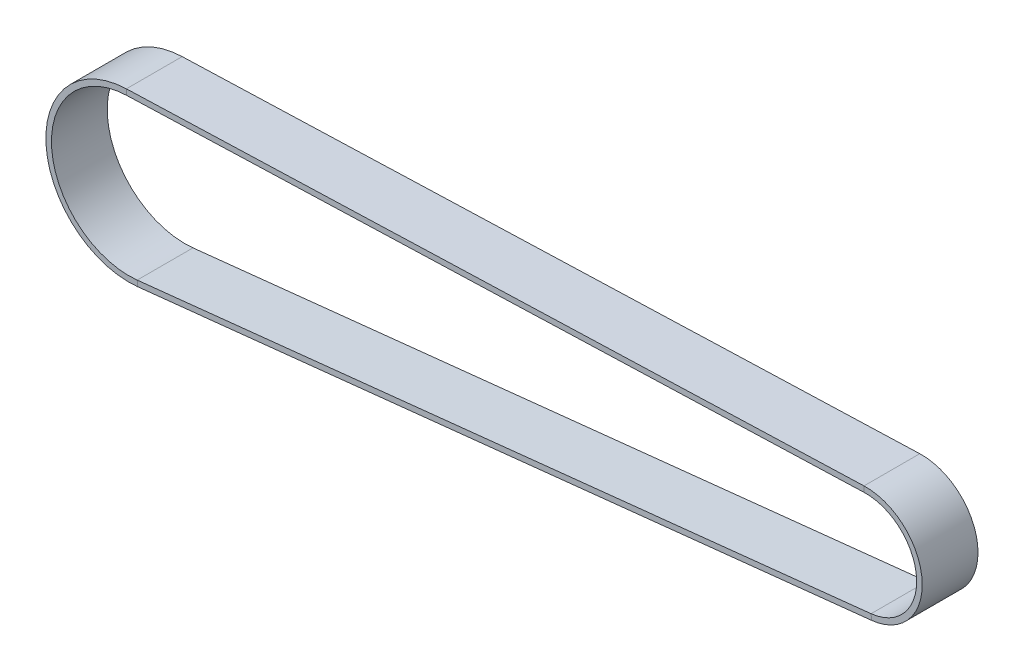
SolidWorks part; units mm, degrees
ref_plane "Alzado" through (0, 0, 0) normal (0, 0, 1) x (1, 0, 0)
ref_plane "Planta" through (0, 0, 0) normal (0, 1, 0) x (1, 0, 0)
ref_plane "Vista lateral" through (0, 0, 0) normal (1, 0, 0) x (0, 0, -1)
sketch "Croquis2" plane through (0, 0, 0) normal (0, 0, 1) x (1, 0, 0)
  line L0 (0, 0) -> (1, 0) construction
  line L1 (0, 0) -> (0, 1) construction
  line L2 (0.9652, -9.0788) -> (-130.6071, -23.0671)
  line L3 (-132.5467, 4.6571) -> (-0.3083, 9.1248)
  arc A0 (-0.3083, 9.1248) -> (0.9652, -9.0788) centre (0, 0) cw
  arc A1 (-130.6071, -23.0671) -> (-132.5467, 4.6571) centre (-132.0772, -9.24) cw
ref_plane "Plano1" through (-0.3083, 0, 0) normal (1, 0, 0) x (0, 0, -1)
sketch "Croquis3" plane through (-0.3083, 0, 0) normal (1, 0, 0) x (0, 0, -1)
  line L1 (-5, 10.1248) -> (5, 10.1248)
  line L2 (-5, 10.1248) -> (-5, 9.1248)
  line L3 (-5, 9.1248) -> (5, 9.1248)
  line L4 (5, 10.1248) -> (5, 9.1248)
  point P4 (0, 9.1248)
  dimension "D1" = 1
  dimension "D2" = 10
sweep "Barrer1" add profiles "Croquis3" path "Croquis2"
